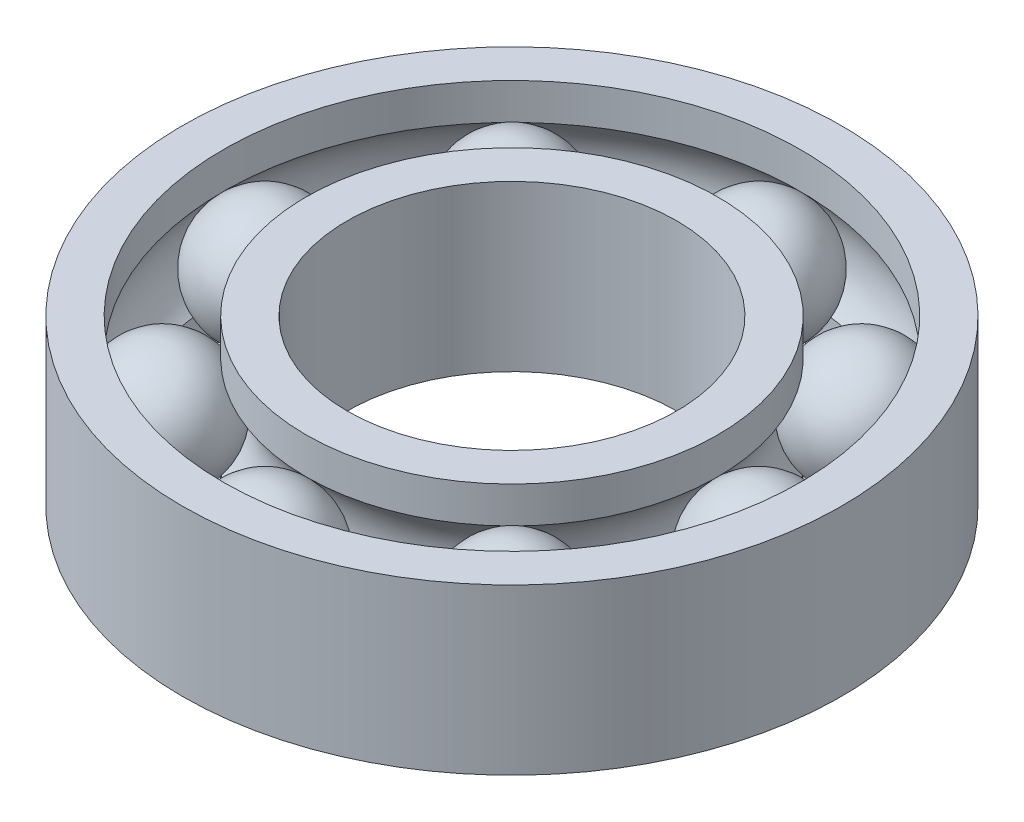
SolidWorks part; units mm, degrees
material "Chrome Stainless Steel"
ref_plane "Front Plane" through (0, 0, 0) normal (0, 0, 1) x (1, 0, 0)
ref_plane "Top Plane" through (0, 0, 0) normal (0, 1, 0) x (1, 0, 0)
ref_plane "Right Plane" through (0, 0, 0) normal (1, 0, 0) x (0, 0, -1)
sketch "Sketch1" plane through (0, 0, 0) normal (0, 0, 1) x (1, 0, 0)
  line L1 (-14, 4) -> (-14, 2.2361)
  line L2 (-8, -4) -> (-8, 4)
  line L3 (-8, -4) -> (-10, -4)
  line L4 (-8, 4) -> (-10, 4)
  line L6 (-10, 4) -> (-10, 2.2361)
  line L8 (-14, -4) -> (-16, -4)
  line L9 (-16, -4) -> (-16, 4)
  line L10 (-10, -2.2361) -> (-10, -4)
  line L11 (-14, -2.2361) -> (-14, -4)
  line L12 (-16, 4) -> (-14, 4)
  arc A6 (-14, 2.2361) -> (-14, -2.2361) centre (-12, 0) ccw
  arc A7 (-10, -2.2361) -> (-10, 2.2361) centre (-12, 0) ccw
  dimension "D5" = 6
  dimension "D1" = 8
  dimension "D2" = 8
  dimension "D3" = 2
  dimension "D4" = 16
sketch "Sketch2" plane through (0, 0, 0) normal (0, 0, 1) x (1, 0, 0)
  line L0 (-11.9938, 3) -> (-11.9938, -3) construction
  line L1 (-11.9938, 3) -> (-11.9938, -3)
  arc A0 (-11.9938, -3) -> (-11.9938, 3) centre (-11.9938, 0) ccw
  dimension "D1" = 3
revolve "Revolve14" add sketch "Sketch2" angle 360 about L0
ref_axis "Axis2" through (0, 8.8, 0) along (0, -1, 0)
revolve "Revolve15" add sketch "Sketch1" angle 360 about axis through (0, 8.8, 0) along (0, -1, 0)
pattern_circular "CirPattern1" count 8 over 360 about axis through (0, 0, 0) along (0, 1, 0) of bodies 118
